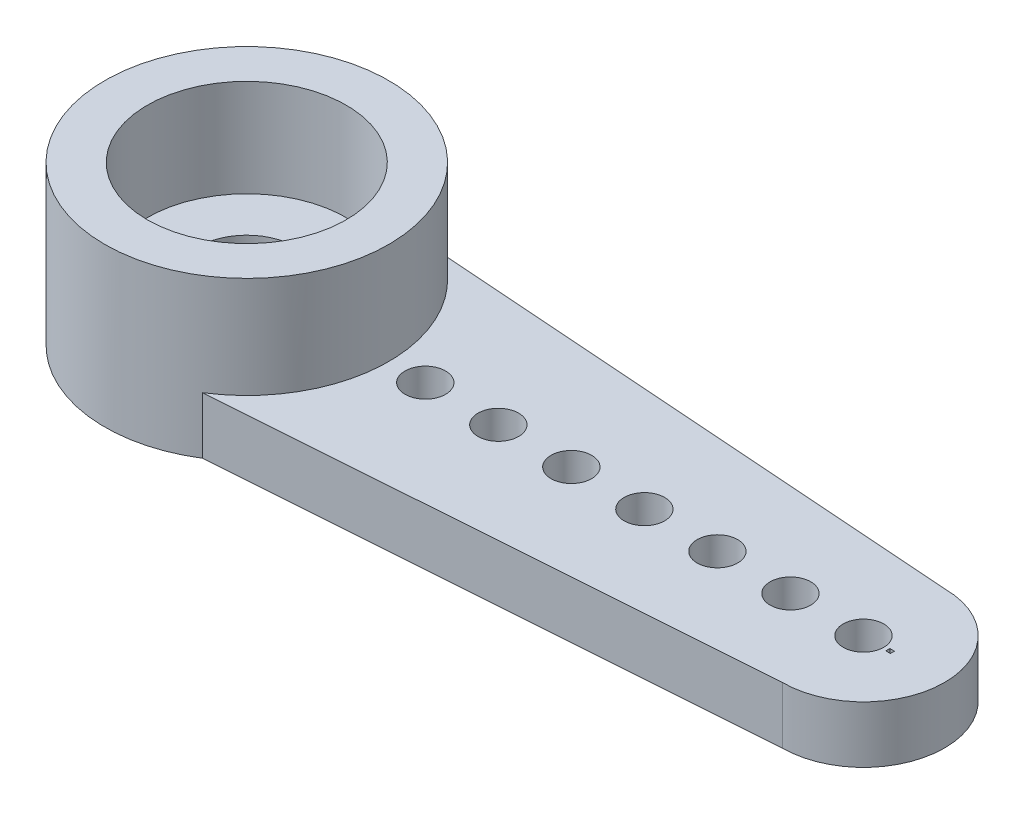
SolidWorks part; units mm, degrees
other "Camera1"
material "ABS"
ref_plane "Front Plane" through (0, 0, 0) normal (0, 0, 1) x (1, 0, 0)
ref_plane "Top Plane" through (0, 0, 0) normal (0, 1, 0) x (1, 0, 0)
ref_plane "Right Plane" through (0, 0, 0) normal (1, 0, 0) x (0, 0, -1)
sketch "Sketch1" plane through (0, 0, 0) normal (0, 1, 0) x (1, 0, 0)
  line L0 (-17.2, 0) -> (17.2, 0) construction
  line L1 (0, -8.35) -> (0, 8.35) construction
  line L2 (-15.2, 2) -> (-2, 2.95)
  line L3 (-15.2, -2) -> (-2, -2.95)
  line L4 (2, 6.35) -> (2, 3.5)
  line L5 (-2, 6.35) -> (-2, 2.95)
  line L6 (2, -6.35) -> (2, -3.5)
  line L7 (-2, -6.35) -> (-2, -2.95)
  line L8 (15.2, 2) -> (2, 3.5)
  line L9 (15.2, -2) -> (2, -3.5)
  circle A0 centre (0, 0) radius 3.5 construction
  arc A1 (-15.2, 2) -> (-15.2, -2) centre (-15.2, 0) ccw
  arc A2 (15.2, 2) -> (15.2, -2) centre (15.2, 0) cw
  arc A3 (2, 6.35) -> (-2, 6.35) centre (0, 6.35) ccw
  circle A4 centre (0, 6.35) radius 0.5
  circle A5 centre (0, 4.55) radius 0.5
  circle A6 centre (0, -4.55) radius 0.5
  circle A7 centre (0, -6.35) radius 0.5
  arc A8 (2, -6.35) -> (-2, -6.35) centre (0, -6.35) cw
  circle A10 centre (-15.2, 0) radius 0.5
  circle A11 centre (15.2, 0) radius 0.5
  circle A12 centre (-13.4, 0) radius 0.5
  circle A13 centre (-11.6, 0) radius 0.5
  circle A14 centre (-9.8, 0) radius 0.5
  circle A15 centre (-8, 0) radius 0.5
  circle A16 centre (-6.2, 0) radius 0.5
  circle A17 centre (-4.4, 0) radius 0.5
  circle A18 centre (13.4, 0) radius 0.5
  circle A19 centre (11.6, 0) radius 0.5
  circle A20 centre (9.8, 0) radius 0.5
  circle A21 centre (8, 0) radius 0.5
  circle A22 centre (6.2, 0) radius 0.5
  circle A23 centre (4.4, 0) radius 0.5
  point P5 (0, 0)
  point P8 (0, 0)
  point P25 (0, 6.85)
  point P26 (0, 4.05)
  dimension "D1" = 7
  dimension "D4" = 4
  dimension "D6" = 1
  dimension "D2" = 34.4
  dimension "D3" = 16.7
  dimension "D5" = 2
  dimension "D7" = 2.8
  dimension "D8" = 7
  dimension "D10" = 5.9
  dimension "D11" = 7
  dimension "D12" = 7
extrude "Boss-Extrude1" add sketch "Sketch1" along normal blind 1.4
sketch "Sketch2" plane through (0, 0, 0) normal (0, -1, 0) x (1, 0, 0)
  circle A0 centre (0, 0) radius 2.35
  dimension "D1" = 4.7
extrude "Cut-Extrude1" cut sketch "Sketch2" against normal blind 1
sketch "Sketch3" plane through (0, 1.4, 0) normal (0, 1, 0) x (1, 0, 0)
  circle A0 centre (0, 0) radius 2.45
  circle A1 centre (0, 0) radius 3.5
  dimension "D1" = 4.9
  dimension "D2" = 7
extrude "Boss-Extrude2" add sketch "Sketch3" along normal blind 2.5
sketch "Sketch4" plane through (0, 1.4, 0) normal (0, 1, 0) x (1, 0, 0)
  circle A0 centre (0, 0) radius 1.2
  dimension "D1" = 2.4
extrude "Cut-Extrude2" cut sketch "Sketch4" against normal through all
sketch "Sketch5" plane through (0, 1.4, 0) normal (0, 1, 0) x (1, 0, 0)
  circle A0 centre (0, 0) radius 1.2 construction
  circle A1 centre (0, 0) radius 2.45
  circle A2 centre (0, 0) radius 2.45
  circle A3 centre (0, 0) radius 1.2
  dimension "D1" = 0
extrude "Boss-Extrude3" add sketch "Sketch5" along normal blind 0.1
sketch "Sketch6" plane through (0, 0, 0) normal (0, -1, 0) x (1, 0, 0)
  line L0 (-2, -2.95) -> (-15.2, -2) construction
  line L1 (-1.8686, -2.9595) -> (-15.2, -2)
  line L2 (-15.2, 2) -> (-2, 2.95) construction
  line L3 (-15.2, 2) -> (-1.8686, 2.9595)
  line L4 (0, -9.3016) -> (0, 8.6978) construction
  line L5 (1.8686, -2.9595) -> (15.2, -2)
  line L6 (15.2, 2) -> (1.8686, 2.9595)
  line L8 (-17.8676, -8.836) -> (17.8676, -8.836)
  line L9 (-17.8676, -8.836) -> (-17.8676, 8.836)
  line L10 (-17.8676, 8.836) -> (17.8676, 8.836)
  line L11 (17.8676, -8.836) -> (17.8676, 8.836)
  line L12 (-17.8676, -8.836) -> (17.8676, 8.836) construction
  line L13 (-17.8676, 8.836) -> (17.8676, -8.836) construction
  arc A0 (-15.2, 2) -> (-15.2, -2) centre (-15.2, 0) ccw construction
  arc A1 (-15.2, 2) -> (-15.2, -2) centre (-15.2, 0) ccw
  circle A2 centre (0, 0) radius 3.5 construction
  arc A3 (1.8686, 2.9595) -> (-1.8686, 2.9595) centre (0, 0) ccw
  arc A4 (15.2, 2) -> (15.2, -2) centre (15.2, 0) cw
  arc A5 (-1.8686, -2.9595) -> (1.8686, -2.9595) centre (0, 0) ccw
extrude "Cut-Extrude4" cut sketch "Sketch6" against normal through all
sketch "Sketch7" plane through (0, 0, 0) normal (0, -1, 0) x (1, 0, 0)
  line L0 (0, 3.5) -> (-17.7318, 3.5)
  line L1 (-17.7318, 3.5) -> (-17.7318, -3.5)
  line L2 (-17.7318, -3.5) -> (0, -3.5)
  circle A0 centre (0, 0) radius 3.5 construction
  arc A1 (0, 3.5) -> (0, -3.5) centre (0, 0) ccw
extrude "Cut-Extrude5" cut sketch "Sketch7" against normal through all
sketch "Sketch8" plane through (0, 1.4, 0) normal (0, 1, 0) x (1, 0, 0)
  line L1 (15.8, -0.05) -> (15.9141, -0.05)
  line L2 (15.8, 0.05) -> (15.9141, 0.05)
  line L3 (15.8, -0.05) -> (15.8, 0.05)
  line L5 (15.8, -0.05) -> (15.9141, -0.05)
  line L6 (15.8, -0.05) -> (15.8, 0.05)
  line L7 (15.8, 0.05) -> (15.9141, 0.05)
  line L8 (15.9141, -0.05) -> (15.9141, 0.05)
extrude "Cut-Extrude6" cut sketch "Sketch8" against normal blind 0.1 contours L1 L8 L2 L3
